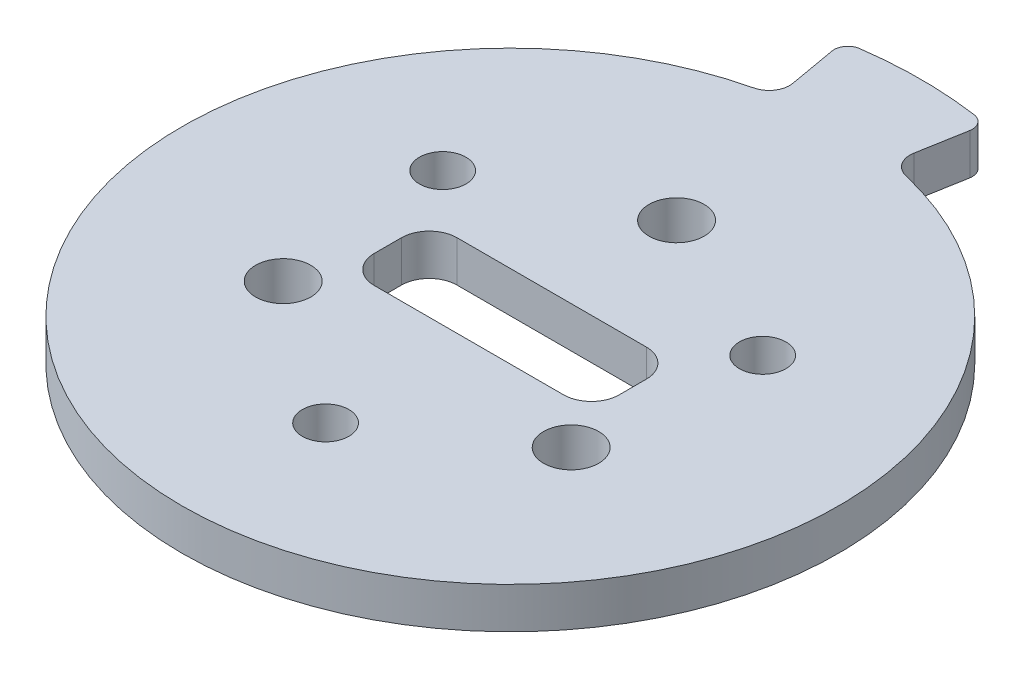
SolidWorks part; units mm, degrees
material "5052-H32"
ref_plane "前视基准面" through (0, 0, 0) normal (0, 0, 1) x (1, 0, 0)
ref_plane "上视基准面" through (0, 0, 0) normal (0, 1, 0) x (1, 0, 0)
ref_plane "右视基准面" through (0, 0, 0) normal (1, 0, 0) x (0, 0, -1)
other "Configuration Table"
sketch "草图1" plane through (0, 0, 0) normal (0, 1, 0) x (1, 0, 0)
  circle A0 centre (0, 0) radius 30
  dimension "D1" = 60
extrude "凸台-拉伸1" add sketch "草图1" along normal blind 3
sketch "草图2" plane through (0, 3, 0) normal (0, 1, 0) x (1, 0, 0)
  line L0 (0, 0) -> (0, -13.5) construction
  line L1 (0, 0) -> (10.5222, -6.075) construction
  circle A0 centre (0, 0) radius 13.5 construction
  circle A1 centre (0, -13.5) radius 1.7
  circle A2 centre (-11.6913, 6.75) radius 1.7
  circle A3 centre (11.6913, 6.75) radius 1.7
  circle A4 centre (0, 0) radius 12.15 construction
  circle A5 centre (10.5222, -6.075) radius 2.015
  circle A6 centre (-10.5222, -6.075) radius 2.015
  circle A7 centre (0, 12.15) radius 2.015
  point P12 (0, 0)
  point P20 (0, 0)
  dimension "D1" = 27
  dimension "D2" = 3.4
  dimension "D4" = 24.3
  dimension "D5" = 4.03
  dimension "D6" = 60
  dimension "D3" = 3
  dimension "D7" = 3
extrude "切除-拉伸1" cut sketch "草图2" against normal blind 3
sketch "草图3" plane through (0, 3, 0) normal (0, 1, 0) x (1, 0, 0)
  line L0 (0, 0) -> (0, 30) construction
  line L1 (0, 0) -> (-5.2094, 29.5442) construction
  line L2 (0, 0) -> (5.2094, 29.5442) construction
  line L3 (-5.2094, 29.5442) -> (-4.1676, 23.6354)
  line L4 (5.2094, 29.5442) -> (4.1676, 23.6354)
  arc A0 (-4.1676, 23.6354) -> (4.1676, 23.6354) centre (0, 0) ccw
  circle A1 centre (0, 0) radius 30 construction
  arc A2 (-5.2094, 29.5442) -> (5.2094, 29.5442) centre (0, 0) ccw
  dimension "D1" = 48
  dimension "D2" = 20
extrude "切除-拉伸2" cut sketch "草图3" against normal blind 3
fillet "圆角1" radius 1.5 2 edges at (4.1676, 1.5, -23.6354) (-4.1676, 1.5, -23.6354)
fillet "圆角2" radius 1 2 edges at (5.2094, 1.5, -29.5442) (-5.2094, 1.5, -29.5442)
sketch "草图4" plane through (0, 3, 0) normal (0, 1, 0) x (1, 0, 0)
  line L1 (-8.95, 3.025) -> (8.95, 3.025)
  line L2 (-8.95, 3.025) -> (-8.95, -3.025)
  line L3 (-8.95, -3.025) -> (8.95, -3.025)
  line L4 (8.95, 3.025) -> (8.95, -3.025)
  line L5 (-8.95, 3.025) -> (8.95, -3.025) construction
  line L6 (-8.95, -3.025) -> (8.95, 3.025) construction
  point P0 (0, 0)
  dimension "D1" = 6.05
  dimension "D2" = 17.9
extrude "切除-拉伸3" cut sketch "草图4" against normal blind 10
fillet "圆角3" radius 2.03 4 edges at (8.95, 1.5, 3.025) (8.95, 1.5, -3.025) (-8.95, 1.5, 3.025) (-8.95, 1.5, -3.025)
